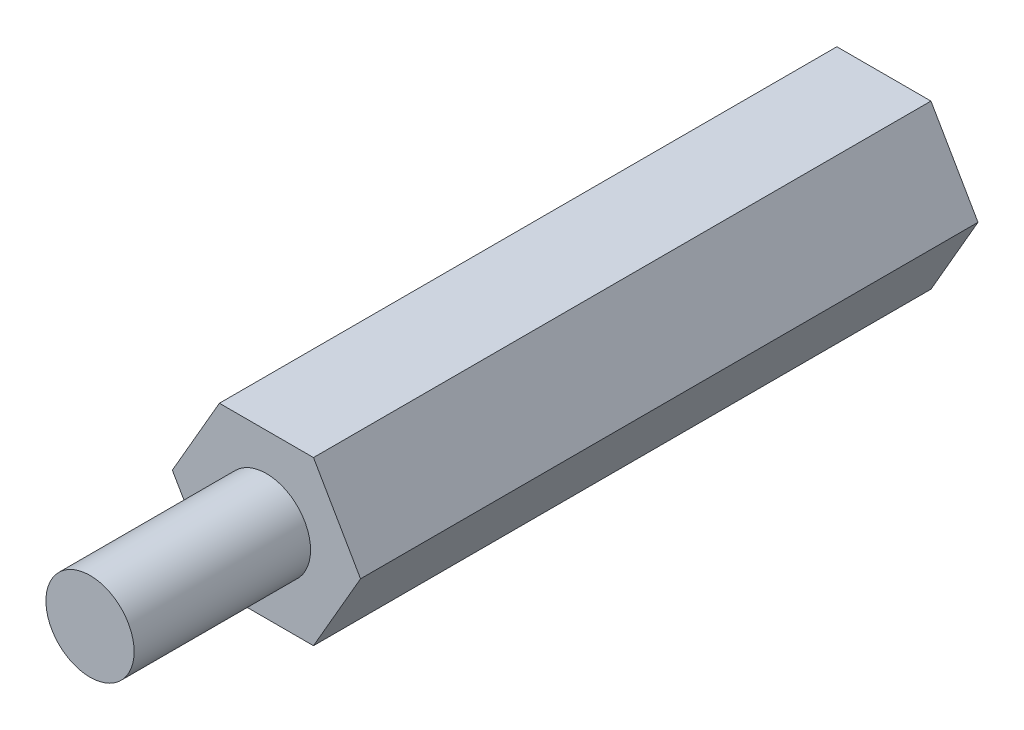
SolidWorks part; units mm, degrees
material "黄铜"
ref_plane "前视基准面" through (0, 0, 0) normal (0, 0, 1) x (1, 0, 0)
ref_plane "上视基准面" through (0, 0, 0) normal (0, 1, 0) x (1, 0, 0)
ref_plane "右视基准面" through (0, 0, 0) normal (1, 0, 0) x (0, 0, -1)
sketch "草图3" plane through (0, 0, 0) normal (0, 0, 1) x (1, 0, 0)
  line L1 (1.6, 2.7713) -> (-1.6, 2.7713)
  line L2 (-1.6, 2.7713) -> (-3.2, 0)
  line L3 (-3.2, 0) -> (-1.6, -2.7713)
  line L4 (-1.6, -2.7713) -> (1.6, -2.7713)
  line L5 (1.6, -2.7713) -> (3.2, 0)
  line L6 (3.2, 0) -> (1.6, 2.7713)
  circle A0 centre (0, 0) radius 2.7713 construction
  dimension "D1" = 3.2
extrude "凸台-拉伸1" add sketch "草图3" along normal blind 21
sketch "草图4" plane through (0, 0, 0) normal (0, 0, -1) x (-1, 0, 0)
  circle A0 centre (0, 0) radius 1.5
  dimension "D1" = 3
extrude "切除-拉伸1" cut sketch "草图4" against normal blind 6
sketch "草图5" plane through (0, 0, 21) normal (0, 0, 1) x (1, 0, 0)
  circle A0 centre (0, 0) radius 1.5
  dimension "D1" = 3
extrude "凸台-拉伸2" add sketch "草图5" along normal blind 6
